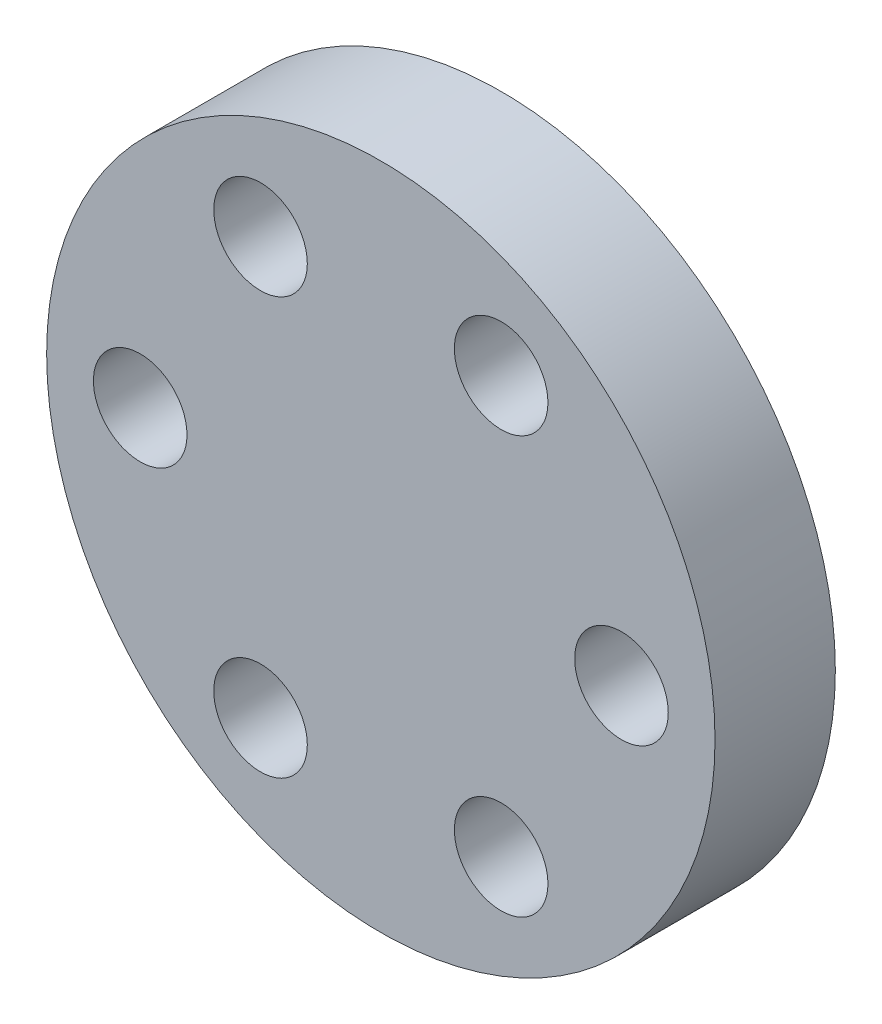
SolidWorks part; units mm, degrees
ref_plane "Front Plane" through (0, 0, 0) normal (1, 0, 0) x (0, 1, 0)
ref_plane "Top Plane" through (0, 0, 0) normal (0, 0, 1) x (0, 1, 0)
ref_plane "Right Plane" through (0, 0, 0) normal (0, 1, 0) x (-1, 0, 0)
sketch "Sketch1" plane through (0, 0, 0) normal (0, 0, 1) x (0, 1, 0)
  circle A0 centre (0, 0) radius 95.25 construction
  circle A1 centre (0, 0) radius 158.75
  circle A2 centre (0, 114.3) radius 22.225
  circle A3 centre (0, 0) radius 114.3 construction
  circle A4 centre (98.9867, 57.15) radius 22.225
  circle A5 centre (98.9867, -57.15) radius 22.225
  circle A6 centre (0, -114.3) radius 22.225
  circle A7 centre (-98.9867, -57.15) radius 22.225
  circle A8 centre (-98.9867, 57.15) radius 22.225
  point P19 (0, 0)
  dimension "D1" = 190.5
  dimension "D2" = 317.5
  dimension "D4" = 44.45
  dimension "D5" = 228.6
  dimension "D3" = 6
extrude "Boss-Extrude1" add sketch "Sketch1" along normal mid plane 57.15
sketch "Sketch2" [suppressed] plane through (0, 0, 28.575) normal (0, 0, 1) x (1, 0, 0)
  line L0 (0, 158.75) -> (0, 0)
  line L1 (0, 0) -> (137.4815, 79.375)
  circle A0 centre (0, 0) radius 158.75 construction
  dimension "D1" = 60
split "Split1" [suppressed] bodies to split 101
